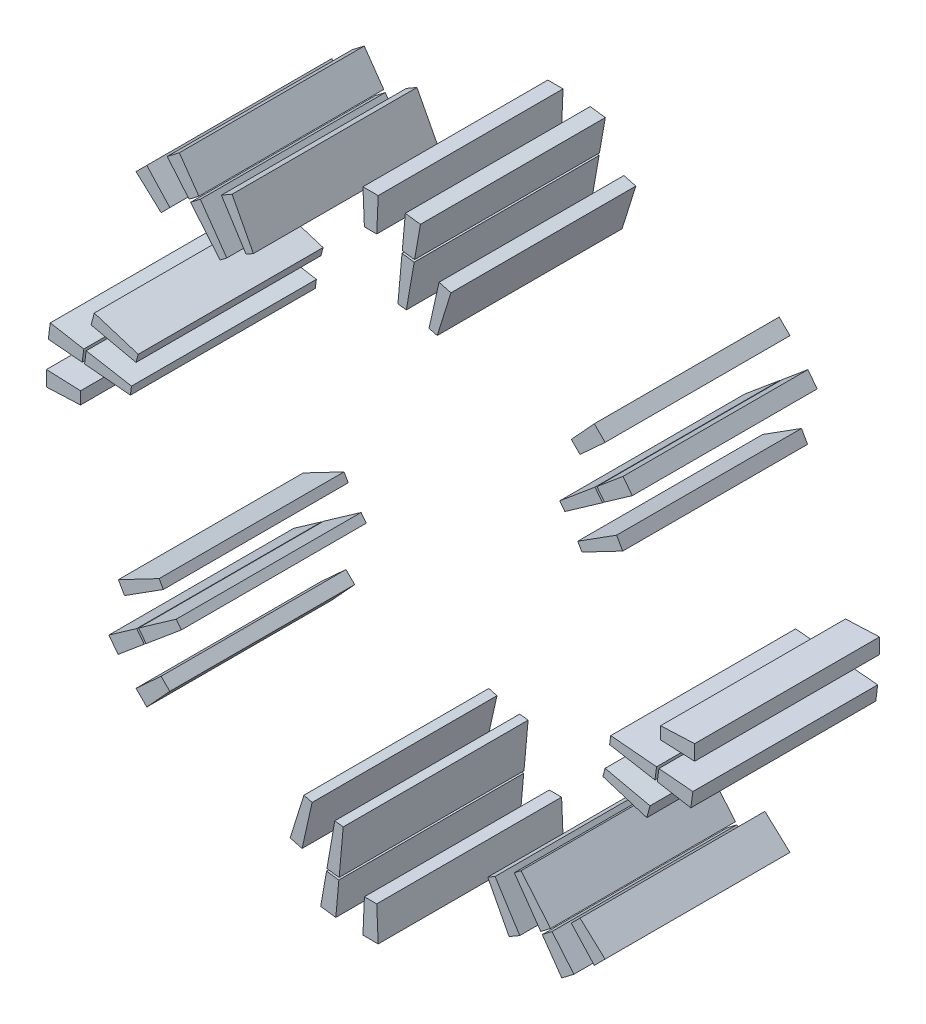
SolidWorks part; units mm, degrees
ref_plane "Спереди" through (0, 0, 0) normal (0, 0, 1) x (1, 0, 0)
ref_plane "Сверху" through (0, 0, 0) normal (0, 1, 0) x (1, 0, 0)
ref_plane "Справа" through (0, 0, 0) normal (1, 0, 0) x (0, 0, -1)
sketch "Эскиз1" plane through (0, 0, 0) normal (0, 0, 1) x (1, 0, 0)
  line L0 (47.0663, -1.0008) -> (52.5846, -1.2375)
  line L1 (52.5846, -1.2375) -> (52.5846, 1.2375)
  line L2 (52.5846, 1.2375) -> (47.0663, 1.0008)
  line L3 (47.0663, 1.0008) -> (47.0663, -1.0008)
  line L4 (34.3067, 19.0131) -> (40.9238, 22.4717)
  line L5 (40.9238, 22.4717) -> (39.923, 24.2052)
  line L6 (39.923, 24.2052) -> (33.6192, 20.2039)
  line L7 (33.6192, 20.2039) -> (34.3067, 19.0131)
  line L8 (37.9495, 27.8581) -> (42.4715, 31.0297)
  line L9 (42.4715, 31.0297) -> (40.9648, 32.9933)
  line L10 (40.9648, 32.9933) -> (36.7309, 29.4462)
  line L11 (36.7309, 29.4462) -> (37.9495, 27.8581)
  line L12 (31.5315, 23.3284) -> (37.6406, 27.6211)
  line L13 (37.6406, 27.6211) -> (36.422, 29.2091)
  line L14 (36.422, 29.2091) -> (30.6945, 24.4193)
  line L15 (30.6945, 24.4193) -> (31.5315, 23.3284)
  line L16 (33.9886, 32.5732) -> (38.058, 36.3079)
  line L17 (38.058, 36.3079) -> (36.3079, 38.058)
  line L18 (36.3079, 38.058) -> (32.5732, 33.9886)
  line L19 (32.5732, 33.9886) -> (33.9886, 32.5732)
  line L20 (10.8142, 37.7028) -> (13.0476, 44.8274)
  line L21 (13.0476, 44.8274) -> (11.1141, 45.3455)
  line L22 (11.1141, 45.3455) -> (9.486, 38.0587)
  line L23 (9.486, 38.0587) -> (10.8142, 37.7028)
  line L24 (7.1357, 46.533) -> (8.0906, 51.9732)
  line L25 (8.0906, 51.9732) -> (5.6368, 52.2963)
  line L26 (5.6368, 52.2963) -> (5.1511, 46.7943)
  line L27 (5.1511, 46.7943) -> (7.1357, 46.533)
  line L28 (5.8005, 38.7918) -> (7.0848, 46.147)
  line L29 (7.0848, 46.147) -> (5.1003, 46.4082)
  line L30 (5.1003, 46.4082) -> (4.4372, 38.9713)
  line L31 (4.4372, 38.9713) -> (5.8005, 38.7918)
  line L32 (1.0008, 47.0663) -> (1.2375, 52.5846)
  line L33 (1.2375, 52.5846) -> (-1.2375, 52.5846)
  line L34 (-1.2375, 52.5846) -> (-1.0008, 47.0663)
  line L35 (-1.0008, 47.0663) -> (1.0008, 47.0663)
  line L36 (-19.0131, 34.3067) -> (-22.4717, 40.9238)
  line L37 (-22.4717, 40.9238) -> (-24.2052, 39.923)
  line L38 (-24.2052, 39.923) -> (-20.2039, 33.6192)
  line L39 (-20.2039, 33.6192) -> (-19.0131, 34.3067)
  line L40 (-27.8581, 37.9495) -> (-31.0297, 42.4715)
  line L41 (-31.0297, 42.4715) -> (-32.9933, 40.9648)
  line L42 (-32.9933, 40.9648) -> (-29.4462, 36.7309)
  line L43 (-29.4462, 36.7309) -> (-27.8581, 37.9495)
  line L44 (-23.3284, 31.5315) -> (-27.6211, 37.6406)
  line L45 (-27.6211, 37.6406) -> (-29.2091, 36.422)
  line L46 (-29.2091, 36.422) -> (-24.4193, 30.6945)
  line L47 (-24.4193, 30.6945) -> (-23.3284, 31.5315)
  line L48 (-32.5732, 33.9886) -> (-36.3079, 38.058)
  line L49 (-36.3079, 38.058) -> (-38.058, 36.3079)
  line L50 (-38.058, 36.3079) -> (-33.9886, 32.5732)
  line L51 (-33.9886, 32.5732) -> (-32.5732, 33.9886)
  line L52 (-37.7028, 10.8142) -> (-44.8274, 13.0476)
  line L53 (-44.8274, 13.0476) -> (-45.3455, 11.1141)
  line L54 (-45.3455, 11.1141) -> (-38.0587, 9.486)
  line L55 (-38.0587, 9.486) -> (-37.7028, 10.8142)
  line L56 (-46.533, 7.1357) -> (-51.9732, 8.0906)
  line L57 (-51.9732, 8.0906) -> (-52.2963, 5.6368)
  line L58 (-52.2963, 5.6368) -> (-46.7943, 5.1511)
  line L59 (-46.7943, 5.1511) -> (-46.533, 7.1357)
  line L60 (-38.7918, 5.8005) -> (-46.147, 7.0848)
  line L61 (-46.147, 7.0848) -> (-46.4082, 5.1003)
  line L62 (-46.4082, 5.1003) -> (-38.9713, 4.4372)
  line L63 (-38.9713, 4.4372) -> (-38.7918, 5.8005)
  line L64 (-47.0663, 1.0008) -> (-52.5846, 1.2375)
  line L65 (-52.5846, 1.2375) -> (-52.5846, -1.2375)
  line L66 (-52.5846, -1.2375) -> (-47.0663, -1.0008)
  line L67 (-47.0663, -1.0008) -> (-47.0663, 1.0008)
  line L68 (-34.3067, -19.0131) -> (-40.9238, -22.4717)
  line L69 (-40.9238, -22.4717) -> (-39.923, -24.2052)
  line L70 (-39.923, -24.2052) -> (-33.6192, -20.2039)
  line L71 (-33.6192, -20.2039) -> (-34.3067, -19.0131)
  line L72 (-37.9495, -27.8581) -> (-42.4715, -31.0297)
  line L73 (-42.4715, -31.0297) -> (-40.9648, -32.9933)
  line L74 (-40.9648, -32.9933) -> (-36.7309, -29.4462)
  line L75 (-36.7309, -29.4462) -> (-37.9495, -27.8581)
  line L76 (-31.5315, -23.3284) -> (-37.6406, -27.6211)
  line L77 (-37.6406, -27.6211) -> (-36.422, -29.2091)
  line L78 (-36.422, -29.2091) -> (-30.6945, -24.4193)
  line L79 (-30.6945, -24.4193) -> (-31.5315, -23.3284)
  line L80 (-33.9886, -32.5732) -> (-38.058, -36.3079)
  line L81 (-38.058, -36.3079) -> (-36.3079, -38.058)
  line L82 (-36.3079, -38.058) -> (-32.5732, -33.9886)
  line L83 (-32.5732, -33.9886) -> (-33.9886, -32.5732)
  line L84 (-10.8142, -37.7028) -> (-13.0476, -44.8274)
  line L85 (-13.0476, -44.8274) -> (-11.1141, -45.3455)
  line L86 (-11.1141, -45.3455) -> (-9.486, -38.0587)
  line L87 (-9.486, -38.0587) -> (-10.8142, -37.7028)
  line L88 (-7.1357, -46.533) -> (-8.0906, -51.9732)
  line L89 (-8.0906, -51.9732) -> (-5.6368, -52.2963)
  line L90 (-5.6368, -52.2963) -> (-5.1511, -46.7943)
  line L91 (-5.1511, -46.7943) -> (-7.1357, -46.533)
  line L92 (-5.8005, -38.7918) -> (-7.0848, -46.147)
  line L93 (-7.0848, -46.147) -> (-5.1003, -46.4082)
  line L94 (-5.1003, -46.4082) -> (-4.4372, -38.9713)
  line L95 (-4.4372, -38.9713) -> (-5.8005, -38.7918)
  line L96 (-1.0008, -47.0663) -> (-1.2375, -52.5846)
  line L97 (-1.2375, -52.5846) -> (1.2375, -52.5846)
  line L98 (1.2375, -52.5846) -> (1.0008, -47.0663)
  line L99 (1.0008, -47.0663) -> (-1.0008, -47.0663)
  line L100 (19.0131, -34.3067) -> (22.4717, -40.9238)
  line L101 (22.4717, -40.9238) -> (24.2052, -39.923)
  line L102 (24.2052, -39.923) -> (20.2039, -33.6192)
  line L103 (20.2039, -33.6192) -> (19.0131, -34.3067)
  line L104 (27.8581, -37.9495) -> (31.0297, -42.4715)
  line L105 (31.0297, -42.4715) -> (32.9933, -40.9648)
  line L106 (32.9933, -40.9648) -> (29.4462, -36.7309)
  line L107 (29.4462, -36.7309) -> (27.8581, -37.9495)
  line L108 (23.3284, -31.5315) -> (27.6211, -37.6406)
  line L109 (27.6211, -37.6406) -> (29.2091, -36.422)
  line L110 (29.2091, -36.422) -> (24.4193, -30.6945)
  line L111 (24.4193, -30.6945) -> (23.3284, -31.5315)
  line L112 (32.5732, -33.9886) -> (36.3079, -38.058)
  line L113 (36.3079, -38.058) -> (38.058, -36.3079)
  line L114 (38.058, -36.3079) -> (33.9886, -32.5732)
  line L115 (33.9886, -32.5732) -> (32.5732, -33.9886)
  line L116 (37.7028, -10.8142) -> (44.8274, -13.0476)
  line L117 (44.8274, -13.0476) -> (45.3455, -11.1141)
  line L118 (45.3455, -11.1141) -> (38.0587, -9.486)
  line L119 (38.0587, -9.486) -> (37.7028, -10.8142)
  line L120 (46.533, -7.1357) -> (51.9732, -8.0906)
  line L121 (51.9732, -8.0906) -> (52.2963, -5.6368)
  line L122 (52.2963, -5.6368) -> (46.7943, -5.1511)
  line L123 (46.7943, -5.1511) -> (46.533, -7.1357)
  line L124 (38.7918, -5.8005) -> (46.147, -7.0848)
  line L125 (46.147, -7.0848) -> (46.4082, -5.1003)
  line L126 (46.4082, -5.1003) -> (38.9713, -4.4372)
  line L127 (38.9713, -4.4372) -> (38.7918, -5.8005)
extrude "Slot_copper_envelopes" add sketch "Эскиз1" along normal blind 30 from offset 15 separate body
